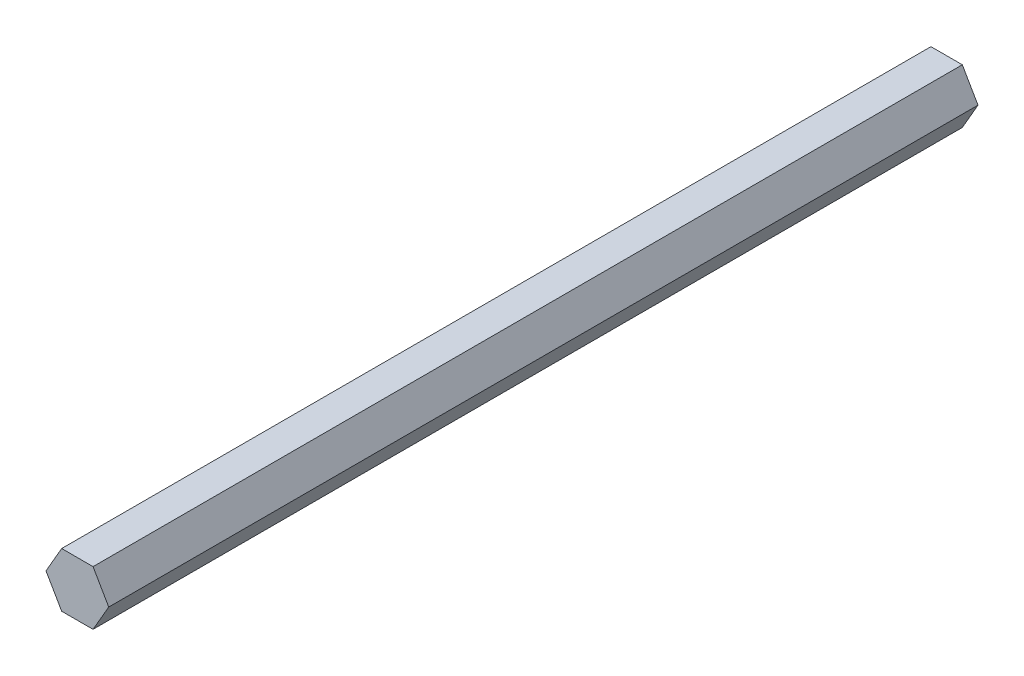
SolidWorks part; units mm, degrees
ref_plane "Front Plane" through (0, 0, 0) normal (0, 0, 1) x (1, 0, 0)
ref_plane "Top Plane" through (0, 0, 0) normal (0, 1, 0) x (1, 0, 0)
ref_plane "Right Plane" through (0, 0, 0) normal (1, 0, 0) x (0, 0, -1)
sketch "Sketch2" plane through (0, 0, 0) normal (0, 0, 1) x (1, 0, 0)
  line L1 (7.3323, 0) -> (3.6662, 6.35)
  line L2 (3.6662, 6.35) -> (-3.6662, 6.35)
  line L3 (-3.6662, 6.35) -> (-7.3323, 0)
  line L4 (-7.3323, 0) -> (-3.6662, -6.35)
  line L5 (-3.6662, -6.35) -> (3.6662, -6.35)
  line L6 (3.6662, -6.35) -> (7.3323, 0)
  circle A0 centre (0, 0) radius 6.35 construction
  dimension "D1" = 12.7
extrude "Boss-Extrude1" add sketch "Sketch2" along normal blind 203.2
